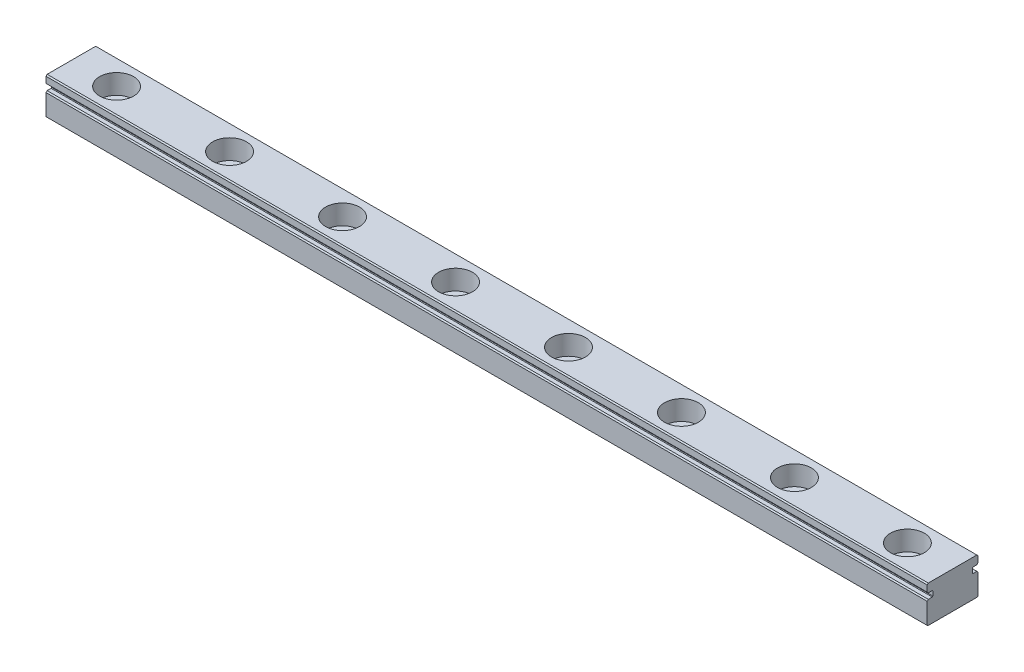
SolidWorks part; units mm, degrees
ref_plane "前视基准面" through (0, 0, 0) normal (0, 0, 1) x (1, 0, 0)
ref_plane "上视基准面" through (0, 0, 0) normal (0, 1, 0) x (1, 0, 0)
ref_plane "右视基准面" through (0, 0, 0) normal (1, 0, 0) x (0, 0, -1)
other "Configuration Table"
sketch "草图1" plane through (0, 0, 0) normal (1, 0, 0) x (0, 0, -1)
  line L0 (-4.5, 1.5) -> (-3.5, 1.5)
  line L1 (-4.5, -3.5) -> (4.5, -3.5)
  line L2 (-4.5, -3.5) -> (-4.5, 0.5)
  line L3 (-4.5, 3) -> (4.5, 3)
  line L4 (4.5, -3.5) -> (4.5, 0.5)
  line L7 (-4.5, 0.5) -> (-3.5, 0.5)
  line L8 (-3.5, 1.5) -> (-3.5, 0.5)
  line L9 (3.5, 1.5) -> (3.5, 0.5)
  line L10 (3.5, 1.5) -> (4.5, 1.5)
  line L11 (3.5, 0.5) -> (4.5, 0.5)
  line L12 (4.5, 1.5) -> (4.5, 3)
  line L13 (-4.5, 1.5) -> (-4.5, 3)
  point P0 (0, 0)
  point P12 (0, 0)
extrude "凸台-拉伸1" add sketch "草图1" along normal blind 156
chamfer "倒角1" distance 0.2 angle 45 6 edges at (78, 0.5, 4.5) (78, 1.5, 4.5) (78, 0.5, -4.5) (78, 1.5, -4.5) (78, 3, -4.5) (78, 3, 4.5)
chamfer "倒角2" distance 0.1 angle 45 6 edges at (78, 0.5, -3.5) (78, 1.5, -3.5) (78, 1.5, 3.5) (78, 0.5, 3.5) (78, -3.5, 4.5) (78, -3.5, -4.5)
sketch "草图2" plane through (0, 3, 0) normal (0, 1, 0) x (1, 0, 0)
  circle A0 centre (8, 0) radius 1.6
  circle A1 centre (28, 0) radius 1.6
  circle A2 centre (48, 0) radius 1.6
  circle A3 centre (68, 0) radius 1.6
  circle A4 centre (88, 0) radius 1.6
  circle A5 centre (108, 0) radius 1.6
  circle A6 centre (128, 0) radius 1.6
  circle A7 centre (148, 0) radius 1.6
  dimension "D1" = 8
extrude "切除-拉伸1" cut sketch "草图2" against normal up to surface (6.5 mm away) up to face at (78, -3.5, 0)
sketch "草图3" plane through (0, 3, 0) normal (0, 1, 0) x (1, 0, 0)
  circle A0 centre (8, 0) radius 3
  circle A1 centre (28, 0) radius 3
  circle A2 centre (48, 0) radius 3
  circle A3 centre (68, 0) radius 3
  circle A4 centre (88, 0) radius 3
  circle A5 centre (108, 0) radius 3
  circle A6 centre (128, 0) radius 3
  circle A7 centre (148, 0) radius 3
  dimension "D1" = 8
extrude "切除-拉伸2" cut sketch "草图3" against normal blind 3.5
